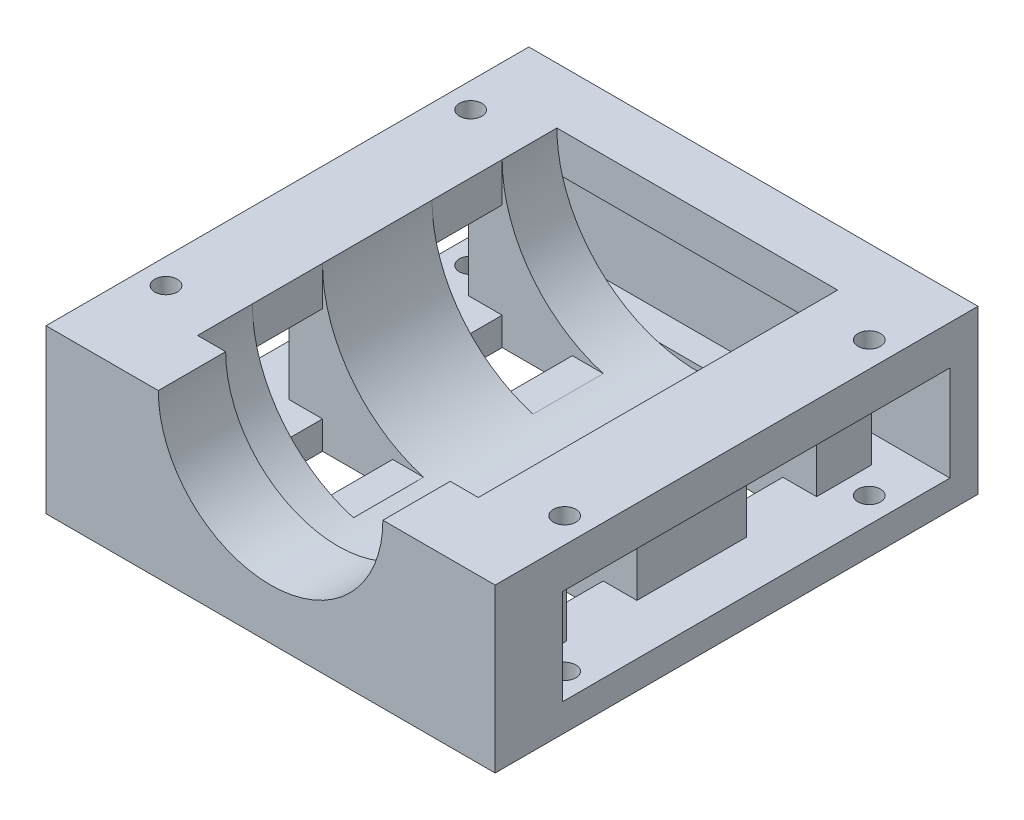
SolidWorks part; units mm, degrees
material "6061 Alloy"
ref_plane "Front Plane" through (0, 0, 0) normal (0, 0, 1) x (1, 0, 0)
ref_plane "Top Plane" through (0, 0, 0) normal (0, 1, 0) x (1, 0, 0)
ref_plane "Right Plane" through (0, 0, 0) normal (1, 0, 0) x (0, 0, -1)
sketch "Sketch1" plane through (0, 0, 0) normal (0, 0, 1) x (1, 0, 0)
  line L0 (0, 0) -> (80, 0)
  line L1 (80, 0) -> (80, 5)
  line L2 (80, 5) -> (71, 5)
  line L3 (71, 5) -> (71, 22)
  line L4 (80, 29) -> (65, 29)
  line L7 (15, 29) -> (0, 29)
  line L8 (9, 22) -> (9, 5)
  line L9 (9, 5) -> (0, 5)
  line L10 (0, 5) -> (0, 0)
  line L12 (0, 29) -> (0, 22)
  line L13 (0, 22) -> (9, 22)
  line L14 (80, 29) -> (80, 22)
  line L15 (80, 22) -> (71, 22)
  arc A0 (15, 29) -> (65, 29) centre (40, 29) ccw
  dimension "D1" = 50
  dimension "D2" = 9
  dimension "D3" = 5
  dimension "D4" = 7
  dimension "D5" = 15
  dimension "D6" = 17
extrude "Boss-Extrude1" add sketch "Sketch1" along normal blind 64
ref_plane "Plane1" through (0, 0, 64) normal (0, 0, 1) x (1, 0, 0)
sketch "Sketch2" plane through (0, 0, 64) normal (0, 0, 1) x (1, 0, 0)
  line L0 (60, 29) -> (80, 29)
  line L1 (0, 0) -> (80, 0)
  line L2 (0, 0) -> (0, 29)
  line L3 (0, 29) -> (20, 29)
  line L4 (80, 0) -> (80, 29)
  line L5 (40, 0) -> (40, 29) construction
  arc A0 (20, 29) -> (60, 29) centre (40, 29) ccw
  dimension "D1" = 40
extrude "Boss-Extrude2" add sketch "Sketch2" along normal blind 12
ref_plane "Plane2" through (0, 29, 0) normal (0, 1, 0) x (1, 0, 0)
sketch "Sketch3" plane through (0, 29, 0) normal (0, 1, 0) x (1, 0, 0)
  line L0 (15, -64) -> (15, 0) construction
  line L1 (15, -9.75) -> (27.5, -9.75)
  line L2 (15, -9.75) -> (15, -22.25)
  line L3 (15, -22.25) -> (27.5, -22.25)
  line L4 (27.5, -9.75) -> (27.5, -22.25)
  line L5 (40, 0) -> (40, -64) construction
  line L6 (65, 0) -> (15, 0) construction
  line L7 (-55, -64) -> (55, -64) construction
  line L8 (40, -32) -> (15, -32) construction
  line L9 (15, 0) -> (65, -64) construction
  line L10 (65, 0) -> (15, -64) construction
  line L11 (15, -32) -> (40, 0) construction
  line L12 (27.5, -16) -> (15, -16) construction
  line L13 (65, -64) -> (65, 0) construction
  line L14 (65, -64) -> (60, -64) construction
  line L15 (65, -22.25) -> (52.5, -22.25)
  line L16 (52.5, -9.75) -> (52.5, -22.25)
  line L17 (65, -9.75) -> (52.5, -9.75)
  line L18 (65, -9.75) -> (65, -22.25)
  line L19 (15, -41.75) -> (27.5, -41.75)
  line L20 (27.5, -54.25) -> (27.5, -41.75)
  line L21 (15, -54.25) -> (27.5, -54.25)
  line L22 (15, -54.25) -> (15, -41.75)
  line L23 (65, -54.25) -> (65, -41.75)
  line L24 (65, -54.25) -> (52.5, -54.25)
  line L25 (52.5, -54.25) -> (52.5, -41.75)
  line L26 (65, -41.75) -> (52.5, -41.75)
  point P23 (15, -16)
extrude "Cut-Extrude1" cut sketch "Sketch3" against normal up to surface (29 mm away) up to face at (40, 0, 38)
ref_plane "Plane3" through (15, 0, 0) normal (1, 0, 0) x (0, 0, -1)
sketch "Sketch5" plane through (15, 0, 0) normal (1, 0, 0) x (0, 0, -1)
  line L0 (-54.25, 0) -> (-54.25, 29) construction
  line L1 (-54.25, 22) -> (-41.75, 22)
  line L2 (-54.25, 22) -> (-54.25, 5)
  line L3 (-54.25, 5) -> (-41.75, 5)
  line L4 (-41.75, 22) -> (-41.75, 5)
  line L5 (-41.75, 0) -> (-41.75, 29) construction
  line L8 (-54.25, 22) -> (-54.25, 29) construction
  line L9 (-54.25, 0) -> (-54.25, 5) construction
  line L16 (-22.25, 22) -> (-9.75, 22)
  line L17 (-22.25, 22) -> (-22.25, 5)
  line L18 (-22.25, 5) -> (-9.75, 5)
  line L19 (-9.75, 22) -> (-9.75, 5)
  line L20 (-22.25, 0) -> (-22.25, 7.3494) construction
  line L21 (-9.75, 0) -> (-9.75, 29) construction
  dimension "D1" = 7
  dimension "D2" = 5
extrude "Cut-Extrude2" cut sketch "Sketch5" against normal up to surface and the other way up to surface up to face at (9, 13.5, 32) other way up to face at (71, 13.5, 32)
ref_plane "Plane4" through (0, 0, 0) normal (0, -1, 0) x (-1, 0, 0)
sketch "Sketch6" plane through (0, 0, 0) normal (0, -1, 0) x (-1, 0, 0)
  line L0 (-4.8728, -32) -> (0, -32) construction
  line L1 (-15, 0) -> (-15, -76) construction
  line L2 (-15, 15.95) -> (-15, -15.95) construction
  line L3 (0, -76) -> (-80, -76) construction
  line L4 (-15, -54.25) -> (0, -64) construction
  line L5 (-27.5, -54.25) -> (-15, -54.25) construction
  line L7 (0, -76) -> (0, 0) construction
  line L9 (0, 0) -> (-80, 0) construction
  line L10 (-40, -76) -> (-40, 0) construction
  line L11 (0, -64) -> (-15, -64) construction
  line L12 (-55, -64) -> (55, -64) construction
  line L13 (0, -64) -> (-15, 0) construction
  line L14 (0, -64) -> (-8.9998, -64) construction
  line L15 (-8.9998, -64) -> (-8.9998, -54.25) construction
  line L16 (-8.9998, -54.25) -> (0, -54.25) construction
  line L17 (0, -54.25) -> (-8.9998, -64) construction
  line L18 (0, -64) -> (-8.9998, -54.25) construction
  circle A0 centre (-4.4999, -59.125) radius 2
  circle A1 centre (-4.4999, -4.875) radius 2
  circle A2 centre (-75.5001, -4.875) radius 2
  circle A3 centre (-75.5001, -59.125) radius 2
  point P13 (-4.4999, -59.125)
  dimension "D1" = 4
extrude "Cut-Extrude3" cut sketch "Sketch6" against normal up to surface (29 mm away) up to face at (67, 29, 40.8)
ref_plane "Plane5" through (0, 0, 0) normal (0, 0, -1) x (-1, 0, 0)
sketch "Sketch7" plane through (0, 0, 0) normal (0, 0, -1) x (-1, 0, 0)
  line L1 (-80, 0) -> (0, 0)
  line L2 (-80, 0) -> (-80, 29)
  line L3 (-80, 29) -> (0, 29)
  line L4 (0, 0) -> (0, 29)
extrude "Boss-Extrude3" add sketch "Sketch7" along normal blind 10
ref_plane "Plane6" through (80, 0, 0) normal (1, 0, 0) x (0, 0, -1)
sketch "Sketch8" plane through (80, 0, 0) normal (1, 0, 0) x (0, 0, -1)
  line L0 (0, 5) -> (10, 5) construction
  line L1 (0, 22) -> (5, 22)
  line L2 (0, 22) -> (0, 5)
  line L3 (0, 5) -> (5, 5)
  line L4 (5, 22) -> (5, 5)
  line L5 (10, 29) -> (10, 0) construction
  line L6 (0, 22) -> (10, 5) construction
  line L8 (0, 5) -> (10, 22) construction
  point P2 (5, 13.5)
  point P12 (5, 13.5)
extrude "Cut-Extrude4" cut sketch "Sketch8" against normal up to surface (80 mm away) up to face at (0, 14.5, 33)
